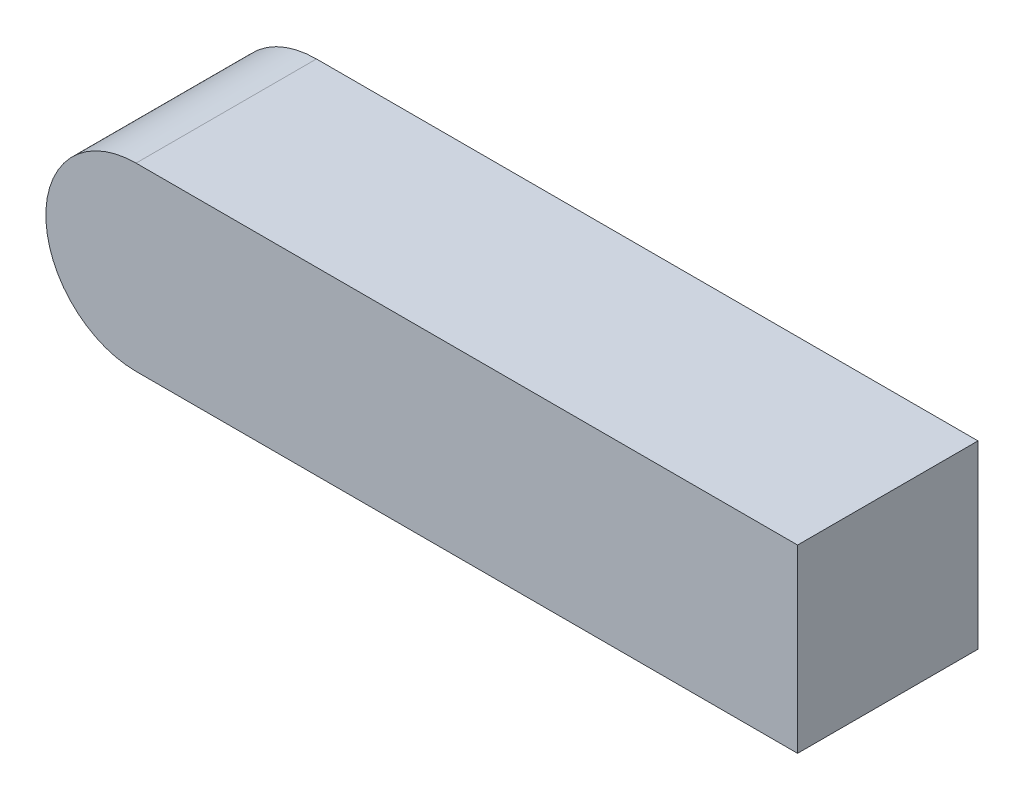
SolidWorks part; units mm, degrees
material "SUS304"
ref_plane "Front Plane" through (0, 0, 0) normal (0, 0, 1) x (1, 0, 0)
ref_plane "Top Plane" through (0, 0, 0) normal (0, 1, 0) x (1, 0, 0)
ref_plane "Right Plane" through (0, 0, 0) normal (1, 0, 0) x (0, 0, -1)
sketch "Sketch1" plane through (0, 0, 0) normal (0, 0, 1) x (1, 0, 0)
  line L0 (-22, 0) -> (0, 0) construction
  line L1 (-22, -3) -> (0, -3)
  line L2 (-22, 3) -> (0, 3)
  line L3 (0, 3) -> (0, -3)
  arc A0 (-22, -3) -> (-22, 3) centre (-22, 0) cw
  arc A1 (0, -3) -> (0, 3) centre (0, 0) ccw construction
  dimension "D3" = 25
  dimension "D1" = 3
  dimension "D2" = 3
extrude "Boss-Extrude1" add sketch "Sketch1" along normal blind 6
equation "\"Mass Kg\"= \"SW-Mass\""
